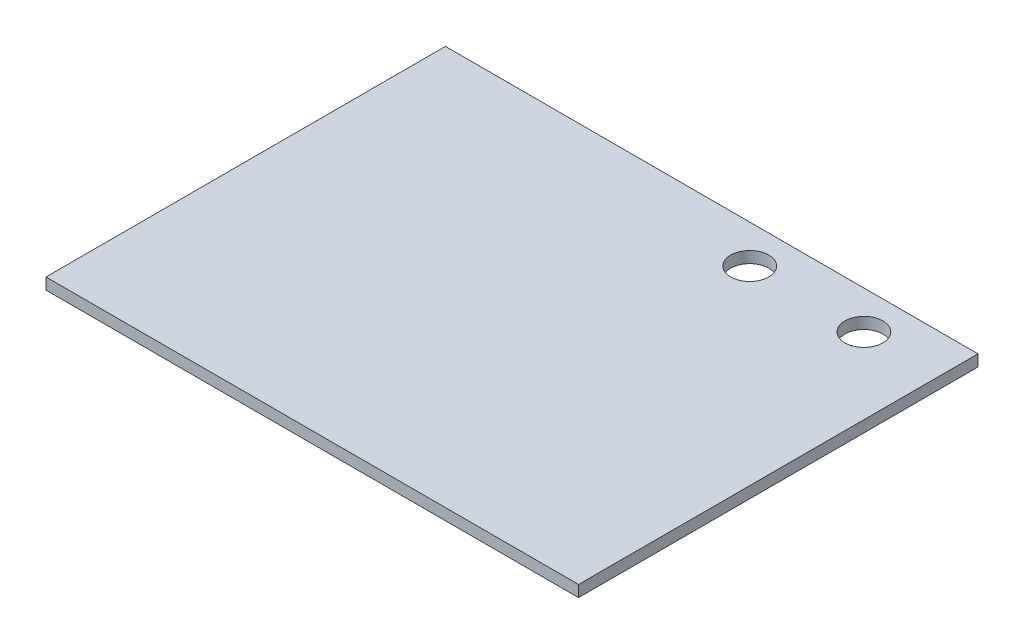
SolidWorks part; units mm, degrees
ref_plane "Front Plane" through (0, 0, 0) normal (0, 0, 1) x (1, 0, 0)
ref_plane "Top Plane" through (0, 0, 0) normal (0, 1, 0) x (1, 0, 0)
ref_plane "Right Plane" through (0, 0, 0) normal (1, 0, 0) x (0, 0, -1)
sketch "Sketch1" plane through (0, 0, 0) normal (0, 1, 0) x (1, 0, 0)
  line L1 (70, -52.5) -> (-70, -52.5)
  line L2 (70, -52.5) -> (70, 52.5)
  line L3 (70, 52.5) -> (-70, 52.5)
  line L4 (-70, -52.5) -> (-70, 52.5)
  line L5 (70, -52.5) -> (-70, 52.5) construction
  line L6 (70, 52.5) -> (-70, -52.5) construction
  point P0 (0, 0)
  dimension "D1" = 105
  dimension "D2" = 140
extrude "Boss-Extrude1" add sketch "Sketch1" along normal blind 3
sketch "Sketch2" plane through (0, 3, 0) normal (0, 1, 0) x (1, 0, 0)
  line L0 (70, -52.5) -> (70, 52.5) construction
  line L1 (70, 52.5) -> (-70, 52.5) construction
  circle A0 centre (50, 42.5) radius 5
  circle A1 centre (20, 42.5) radius 5
  dimension "D1" = 10
  dimension "D4" = 10
  dimension "D2" = 20
  dimension "D3" = 10
  dimension "D5" = 30
  dimension "D6" = 10
extrude "Cut-Extrude1" cut sketch "Sketch2" against normal blind 10
